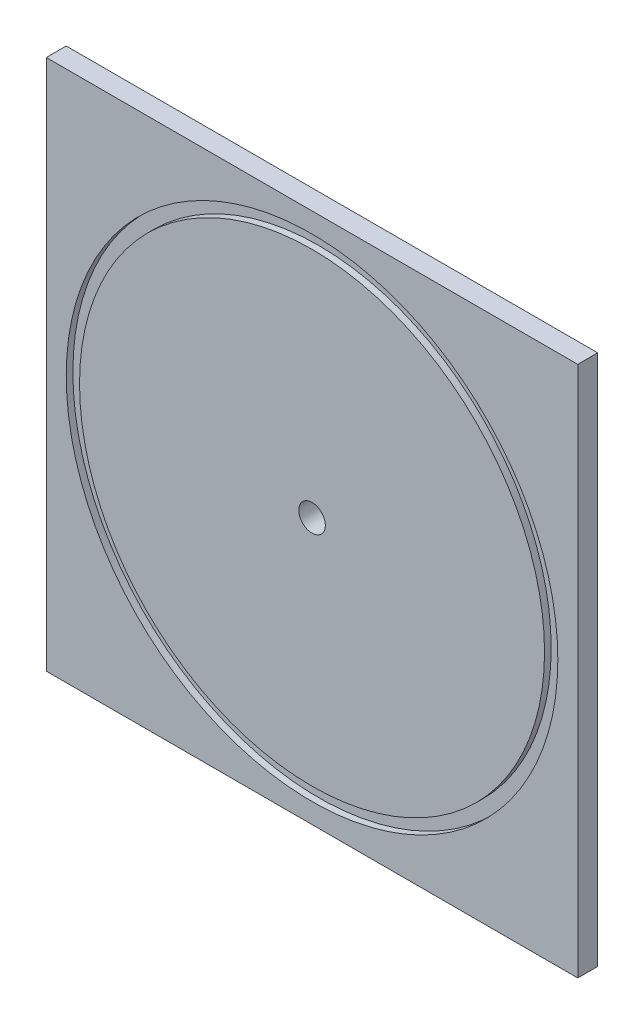
SolidWorks part; units mm, degrees
ref_plane "Front Plane" through (0, 0, 0) normal (0, 0, 1) x (1, 0, 0)
ref_plane "Top Plane" through (0, 0, 0) normal (0, 1, 0) x (1, 0, 0)
ref_plane "Right Plane" through (0, 0, 0) normal (1, 0, 0) x (0, 0, -1)
sketch "Sketch2" plane through (0, 0, 0) normal (0, 0, 1) x (1, 0, 0)
  line L1 (-50.8, -50.8) -> (50.8, -50.8)
  line L2 (-50.8, -50.8) -> (-50.8, 50.8)
  line L3 (-50.8, 50.8) -> (50.8, 50.8)
  line L4 (50.8, -50.8) -> (50.8, 50.8)
  line L5 (-50.8, -50.8) -> (50.8, 50.8) construction
  line L6 (-50.8, 50.8) -> (50.8, -50.8) construction
  point P0 (0, 0)
  dimension "D1" = 101.6
extrude "Sleeve" add sketch "Sketch2" along normal blind 3.81
sketch "Sketch3" plane through (0, 0, 3.81) normal (0, 0, 1) x (1, 0, 0)
  circle A0 centre (0, 0) radius 2.54
  dimension "D1" = 5.08
extrude "Hole" cut sketch "Sketch3" against normal through all
sketch "Sketch4" plane through (0, 0, 3.81) normal (0, 0, 1) x (1, 0, 0)
  circle A0 centre (0, 0) radius 44.45
  dimension "D1" = 88.9
extrude "Vinyl Outline" cut sketch "Sketch4" against normal blind 1.27 thin
